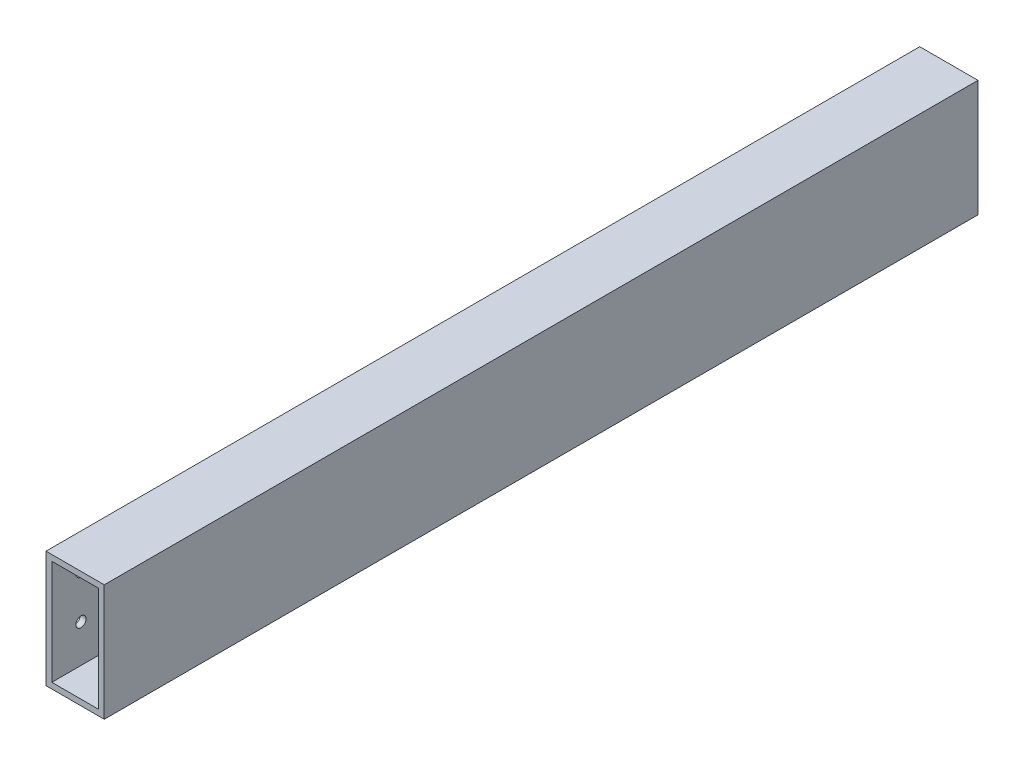
SolidWorks part; units mm, degrees
ref_plane "Plano frontal" through (0, 0, 0) normal (0, 0, 1) x (1, 0, 0)
ref_plane "Plano superior" through (0, 0, 0) normal (0, 1, 0) x (1, 0, 0)
ref_plane "Plano direito" through (0, 0, 0) normal (1, 0, 0) x (0, 0, -1)
sketch "Esboço1" plane through (0, 0, 0) normal (0, 0, 1) x (1, 0, 0)
  line L2 (0, 0) -> (20, 0)
  line L3 (0, 0) -> (0, 40)
  line L4 (0, 40) -> (20, 40)
  line L5 (20, 0) -> (20, 40)
  line L7 (2, 2) -> (18, 2)
  line L8 (2, 2) -> (2, 38)
  line L9 (2, 38) -> (18, 38)
  line L10 (18, 2) -> (18, 38)
  dimension "D1" = 40
  dimension "D2" = 20
  dimension "D3" = 2
  dimension "D4" = 2
  dimension "D5" = 2
  dimension "D6" = 2
extrude "Ressalto-extrusão1" add sketch "Esboço1" along normal blind 300
sketch "Esboço2" plane through (0, 0, 0) normal (-1, 0, 0) x (0, 0, 1)
  line L0 (0, 40) -> (0, 0) construction
  line L1 (300, 0) -> (0, 0) construction
  line L2 (150, 40) -> (150, 0) construction
  line L3 (300, 40) -> (0, 40) construction
  circle A0 centre (10, 30) radius 1.75
  circle A1 centre (10, 15) radius 1.75
  circle A2 centre (70, 15) radius 1.75
  circle A3 centre (55, 15) radius 1.75
  circle A4 centre (230, 15) radius 1.75
  circle A5 centre (245, 15) radius 1.75
  circle A6 centre (290, 15) radius 1.75
  circle A7 centre (290, 30) radius 1.75
  dimension "D1" = 3.5
  dimension "D2" = 3.5
  dimension "D7" = 3.5
  dimension "D8" = 3.5
  dimension "D3" = 10
  dimension "D4" = 15
  dimension "D5" = 15
  dimension "D6" = 10
  dimension "D9" = 70
  dimension "D10" = 15
extrude "Corte-extrusão1" cut sketch "Esboço2" against normal blind 2
